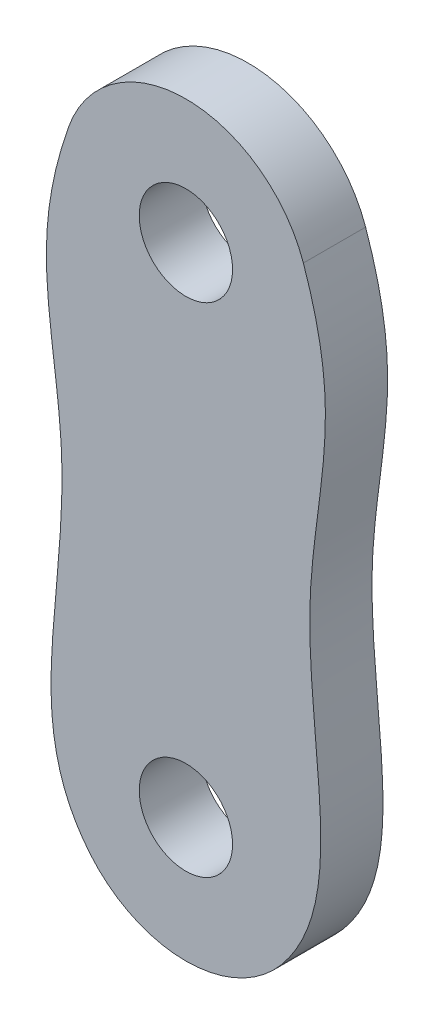
SolidWorks part; units mm, degrees
ref_plane "Front Plane" through (0, 0, 0) normal (0, 0, 1) x (1, 0, 0)
ref_plane "Top Plane" through (0, 0, 0) normal (0, 1, 0) x (1, 0, 0)
ref_plane "Right Plane" through (0, 0, 0) normal (1, 0, 0) x (0, 0, -1)
sketch "Sketch1" plane through (0, 0, 0) normal (0, 0, 1) x (1, 0, 0)
  line L0 (0, 0) -> (0, 3.9028)
  circle A0 centre (0, 0) radius 2.3813
  circle A1 centre (0, 25.4) radius 2.3813
  circle A2 centre (0, 25.4) radius 6.35
  circle A3 centre (0, 0) radius 6.35
  spline S0 degree 3 poles (-5.9951, 27.4932) (-6.6954, 25.4873) (-7.6361, 20.832) (-5.8361, 13.1181) (-6.9798, 4.6235) (-7.0328, -1.4959) (-4.8656, -4.0802) knots 0 0 0 0 0.186999 0.456276 0.716521 1 1 1 1
  spline S1 degree 3 poles (5.9951, 27.4932) (6.6954, 25.4873) (7.6361, 20.832) (5.8361, 13.1181) (6.9798, 4.6235) (7.0328, -1.4959) (4.8656, -4.0802) knots 0 0 0 0 0.186999 0.456276 0.716521 1 1 1 1
  dimension "D1" = 4.7625
  dimension "D2" = 4.7625
  dimension "D4" = 12.7
  dimension "D5" = 12.7
  dimension "D3" = 25.4
extrude "Boss-Extrude1" add sketch "Sketch1" along normal blind 3.175
